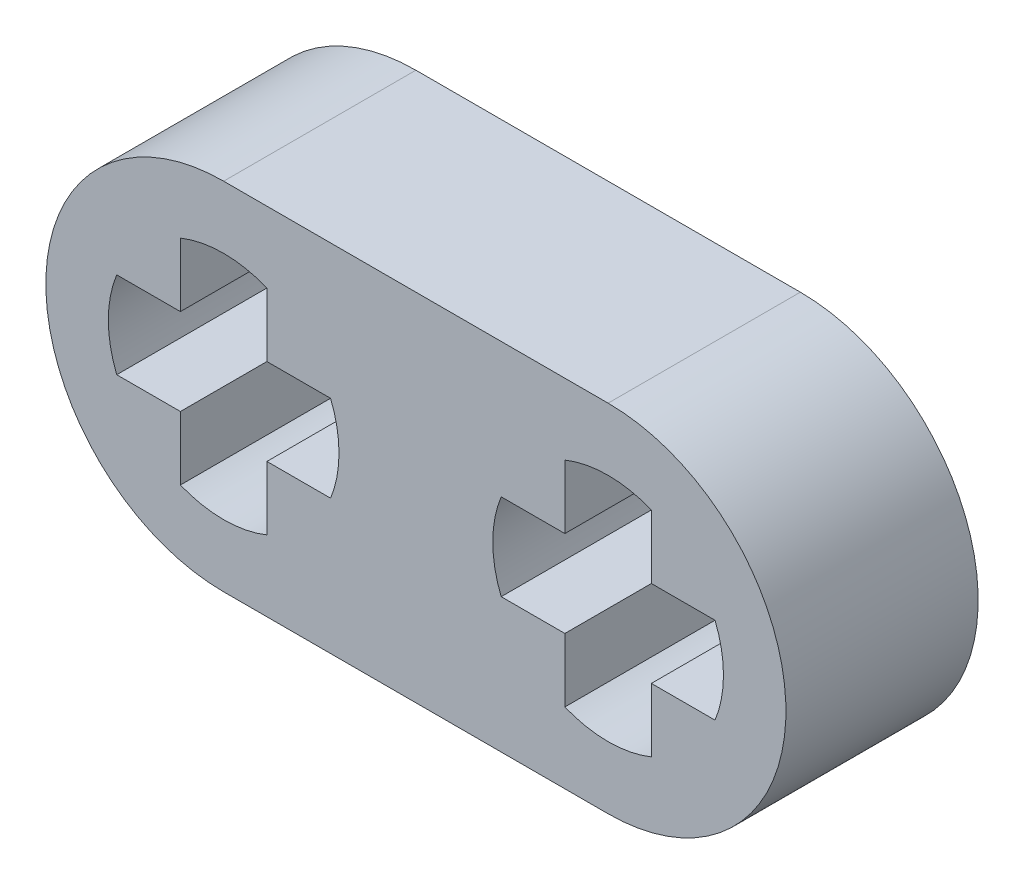
SolidWorks part; units mm, degrees
ref_plane "Front Plane" through (0, 0, 0) normal (0, 0, 1) x (1, 0, 0)
ref_plane "Top Plane" through (0, 0, 0) normal (0, 1, 0) x (1, 0, 0)
ref_plane "Right Plane" through (0, 0, 0) normal (1, 0, 0) x (0, 0, -1)
sketch "Sketch1" plane through (0, 0, 0) normal (0, 0, 1) x (1, 0, 0)
  line L0 (4, 0) -> (-4, 0) construction
  line L1 (4, -3.7) -> (-4, -3.7)
  line L2 (4, 3.7) -> (-4, 3.7)
  line L3 (0, 0) -> (0, 3.7) construction
  line L4 (4.9, -2.4) -> (3.1, -2.4)
  line L5 (4.9, -2.4) -> (4.9, 2.4)
  line L6 (4.9, 2.4) -> (3.1, 2.4)
  line L7 (3.1, -2.4) -> (3.1, 2.4)
  line L8 (4.9, -2.4) -> (3.1, 2.4) construction
  line L9 (4.9, 2.4) -> (3.1, -2.4) construction
  line L10 (6.4, -0.9) -> (1.6, -0.9)
  line L11 (6.4, -0.9) -> (6.4, 0.9)
  line L12 (6.4, 0.9) -> (1.6, 0.9)
  line L13 (1.6, -0.9) -> (1.6, 0.9)
  line L14 (6.4, -0.9) -> (1.6, 0.9) construction
  line L15 (6.4, 0.9) -> (1.6, -0.9) construction
  line L16 (-6.4, -0.9) -> (-6.4, 0.9)
  line L17 (-6.4, -0.9) -> (-1.6, -0.9)
  line L18 (-1.6, -0.9) -> (-1.6, 0.9)
  line L19 (-6.4, 0.9) -> (-1.6, 0.9)
  line L20 (-4.9, -2.4) -> (-3.1, -2.4)
  line L21 (-3.1, -2.4) -> (-3.1, 2.4)
  line L22 (-4.9, 2.4) -> (-3.1, 2.4)
  line L23 (-4.9, -2.4) -> (-4.9, 2.4)
  arc A0 (4, -3.7) -> (4, 3.7) centre (4, 0) ccw
  arc A1 (-4, 3.7) -> (-4, -3.7) centre (-4, 0) ccw
  circle A2 centre (4, 0) radius 2.4
  circle A3 centre (-4, 0) radius 2.4
  point P2 (0, 0)
  dimension "D2" = 15.4
  dimension "D3" = 4.8
  dimension "D1" = 7.4
  dimension "D4" = 1.8
  dimension "D5" = 8
extrude "Boss-Extrude1" add sketch "Sketch1" along normal mid plane 4 contours L2 A1 L1 A0 A2 L12 L11 L10 L5 L4 L7 L13 L6 L17 A3 L21 L20 L23 L16 L19 L22 L18 | L23 A3 L22 | L22 A3 L21 | A3 L21 L19 | A3 L19 L23 | A3 L17 L21 | A3 L23 L17 | L19 A3 L18 | L18 A3 L17 | L21 A3 L20 | L20 A3 L23 | L17 A3 L16 | L16 A3 L19 | L12 A2 L5 | L7 A2 L12 | L10 A2 L7 | L5 A2 L10 | A2 L4 L5 | A2 L7 L4 | A2 L10 L11 | A2 L11 L12 | A2 L5 L6 | A2 L6 L7 | A2 L13 L10 | A2 L12 L13
